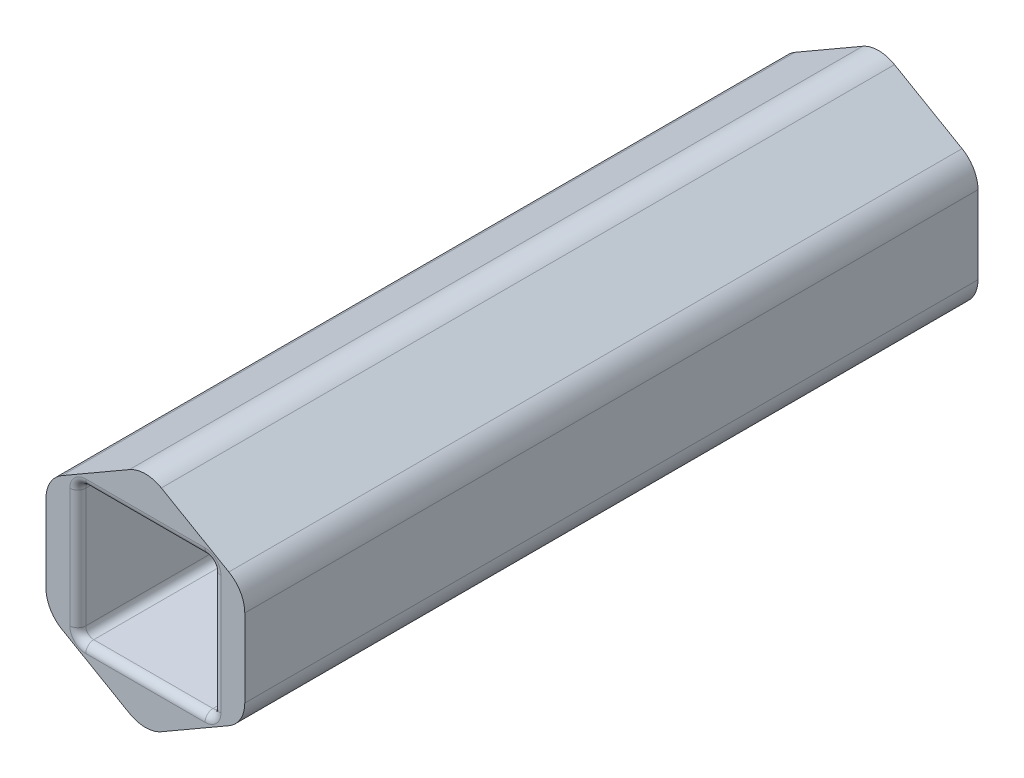
SolidWorks part; units mm, degrees
ref_plane "Front Plane" through (0, 0, 0) normal (0, 0, 1) x (1, 0, 0)
ref_plane "Top Plane" through (0, 0, 0) normal (0, 1, 0) x (1, 0, 0)
ref_plane "Right Plane" through (0, 0, 0) normal (1, 0, 0) x (0, 0, -1)
other "Configuration Table"
sketch "Sketch1" plane through (0, 0, 0) normal (0, 0, 1) x (1, 0, 0)
  line L1 (-3.3655, -3.3655) -> (3.3655, -3.3655)
  line L2 (-3.3655, -3.3655) -> (-3.3655, 3.3655)
  line L3 (-3.3655, 3.3655) -> (3.3655, 3.3655)
  line L4 (3.3655, -3.3655) -> (3.3655, 3.3655)
  line L5 (-3.3655, -3.3655) -> (3.3655, 3.3655) construction
  line L6 (-3.3655, 3.3655) -> (3.3655, -3.3655) construction
  line L7 (4.9493, -2.8575) -> (4.9493, 2.8575)
  line L8 (4.9493, 2.8575) -> (0, 5.715)
  line L9 (0, 5.715) -> (-4.9493, 2.8575)
  line L10 (-4.9493, 2.8575) -> (-4.9493, -2.8575)
  line L11 (-4.9493, -2.8575) -> (0, -5.715)
  line L12 (0, -5.715) -> (4.9493, -2.8575)
  circle A0 centre (0, 0) radius 4.9493 construction
  point P0 (0, 0)
  point P7 (0, 0)
  point P15 (0, 0)
  point P16 (-0.0311, 5.7461)
  point P17 (0, 0)
  point P18 (0, 0)
  dimension "D1" = 6.731
  dimension "D2" = 5.715
extrude "Boss-Extrude1" add sketch "Sketch1" along normal blind 36.5125
fillet "Fillet1" radius 0.3969 12 edges at (0, 3.3655, 36.5125) (0, 3.3655, 0) (-3.3655, 0, 36.5125) (-3.3655, 3.3655, 18.2562) (-3.3655, 0, 0) (0, -3.3655, 36.5125) (-3.3655, -3.3655, 18.2562) (0, -3.3655, 0) (3.3655, 3.3655, 18.2562) (3.3655, 0, 36.5125) (3.3655, -3.3655, 18.2562) (3.3655, 0, 0)
fillet "Fillet2" radius 1.5875 6 edges at (4.9493, 2.8575, 18.2562) (4.9493, -2.8575, 18.2562) (0, -5.715, 18.2562) (-4.9493, -2.8575, 18.2562) (-4.9493, 2.8575, 18.2562) (0, 5.715, 18.2562)
